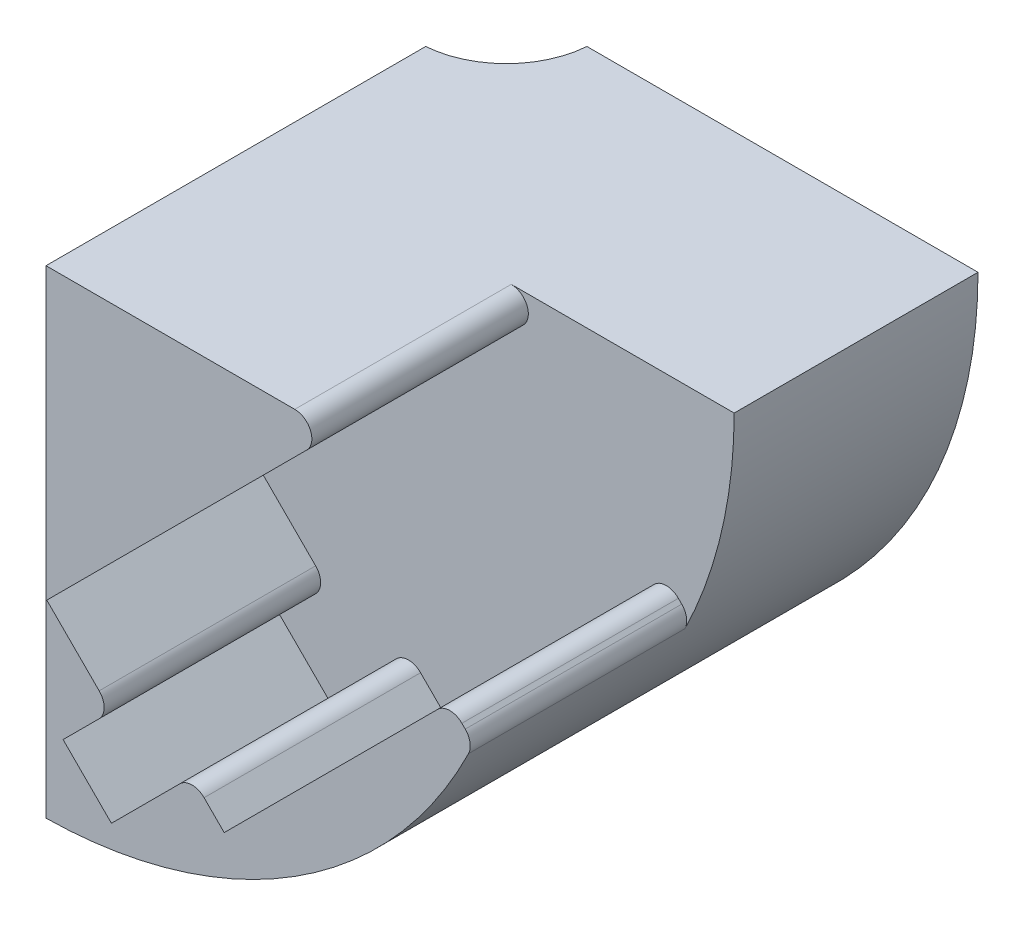
SolidWorks part; units mm, degrees
ref_plane "Front Plane" through (0, 0, 0) normal (0, 0, 1) x (1, 0, 0)
ref_plane "Top Plane" through (0, 0, 0) normal (0, 1, 0) x (1, 0, 0)
ref_plane "Right Plane" through (0, 0, 0) normal (1, 0, 0) x (0, 0, -1)
sketch "Sketch1" plane through (0, 0, 0) normal (0, 0, 1) x (1, 0, 0)
  circle A0 centre (0, 0) radius 42
  dimension "D1" = 84
extrude "Boss-Extrude1" add sketch "Sketch1" along normal blind 41
sketch "Sketch2" plane through (0, 0, 41) normal (0, 0, 1) x (1, 0, 0)
  line L0 (0, 0) -> (42, 0)
  line L1 (0, 0) -> (0, -42)
  circle A0 centre (0, 0) radius 42 construction
  arc A1 (42, 0) -> (0, -42) centre (0, 0) ccw
extrude "Cut-Extrude1" cut sketch "Sketch2" against normal through all
sketch "Sketch3" plane through (0, 0, 0) normal (0, 1, 0) x (1, 0, 0)
  circle A0 centre (0, 0) radius 7.7
  dimension "D1" = 15.4
extrude "Cut-Extrude2" cut sketch "Sketch3" against normal through all
sketch "Sketch4" plane through (0, 0, 0) normal (0, 1, 0) x (1, 0, 0)
  line L1 (0, -41) -> (0.6, -41)
  line L2 (0, -41) -> (0, -6.788)
  line L3 (0, -6.788) -> (0.6, -6.788)
  line L4 (0.6, -41) -> (0.6, -6.788)
  line L5 (42, 0) -> (6.2585, 0)
  line L6 (42, 0) -> (42, -0.6)
  line L7 (42, -0.6) -> (6.2585, -0.6)
  line L8 (6.2585, 0) -> (6.2585, -0.6)
  dimension "D1" = 0.6
  dimension "D2" = 0.6
extrude "Cut-Extrude3" cut sketch "Sketch4" against normal through all
sketch "Sketch5" plane through (0, 0, 41) normal (0, 0, 1) x (1, 0, 0)
  line L0 (26.0558, 0) -> (0.6, -25.4558)
  line L1 (26.0558, 0) -> (31.7127, -5.6569)
  line L2 (0.6, -25.4558) -> (6.2569, -31.1127)
  line L3 (31.7127, -5.6569) -> (6.2569, -31.1127)
  line L4 (0.6, 0) -> (42, 0) construction
  line L5 (0.6, -41.9957) -> (0.6, 0) construction
  line L6 (38.1624, -7.6924) -> (6.3426, -39.5122)
  line L7 (38.1624, -7.6924) -> (33.9198, -3.4497)
  line L8 (6.3426, -39.5122) -> (2.1, -35.2696)
  line L9 (33.9198, -3.4497) -> (2.1, -35.2696)
  line L10 (26.0558, 0) -> (0.6, 0) construction
  line L11 (0.6, 0) -> (0.6, -25.4558) construction
  line L12 (33.2127, -12.6421) -> (13.4137, -32.4411)
  line L13 (33.2127, -12.6421) -> (36.0411, -15.4706)
  line L14 (13.4137, -32.4411) -> (16.2421, -35.2696)
  line L15 (36.0411, -15.4706) -> (16.2421, -35.2696)
  dimension "D1" = 8
  dimension "D2" = 36
  dimension "D3" = 45
  dimension "D4" = 6
  dimension "D5" = 1.5
  dimension "D6" = 4
  dimension "D7" = 28
  dimension "D8" = 10
extrude "Cut-Extrude4" cut sketch "Sketch5" against normal blind 19 contours L15 L13 L6 L14 | L7 L9 L3 L8 L6
sketch "Sketch6" plane through (0, 0, 41) normal (0, 0, 1) x (1, 0, 0)
  line L0 (28.9701, -8.3995) -> (6.3276, -31.042)
  line L2 (6.3276, -31.042) -> (0.6707, -25.3851)
  line L3 (26.0558, 0) -> (0.6707, -25.3851)
  line L4 (33.9198, -3.4497) -> (2.1, -35.2696) construction
  line L5 (33.9198, -3.4497) -> (2.1, -35.2696) construction
  line L6 (0.6, 0) -> (42, 0) construction
  line L7 (26.0558, 0) -> (42, 0)
  line L10 (33.2127, -12.6421) -> (38.1459, -17.5753)
  line L11 (33.2127, -12.6421) -> (28.9701, -8.3995)
  line L12 (33.2127, -12.6421) -> (36.0411, -15.4706) construction
  arc A0 (0.6, -41.9957) -> (42, 0) centre (0, 0) ccw construction
  arc A2 (38.1459, -17.5753) -> (42, 0) centre (0, 0) ccw
  dimension "D1" = 35.9
  dimension "D2" = 8
extrude "Cut-Extrude6" cut sketch "Sketch6" against normal up to surface (19 mm away) up to face at (22.4293, -22.7184, 22)
fillet "Fillet1" radius 1.5 5 edges at (6.3276, -31.042, 31.5) (13.4137, -32.4411, 31.5) (26.0558, 0, 31.5) (38.1459, -17.5753, 31.5) (36.0411, -15.4706, 31.5)
